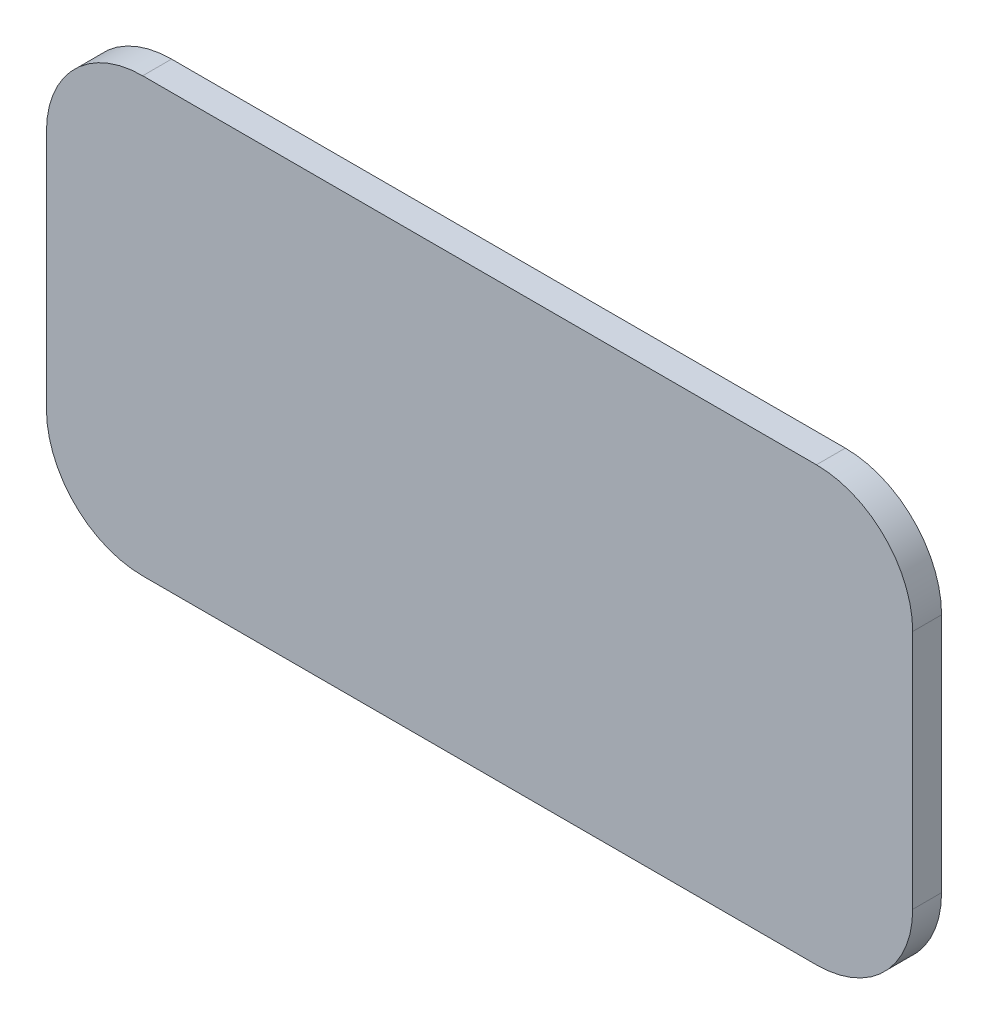
SolidWorks part; units mm, degrees
material "Du"
ref_plane "Front Plane" through (0, 0, 0) normal (0, 0, 1) x (1, 0, 0)
ref_plane "Top Plane" through (0, 0, 0) normal (0, 1, 0) x (1, 0, 0)
ref_plane "Right Plane" through (0, 0, 0) normal (1, 0, 0) x (0, 0, -1)
sketch "Sketch1" plane through (0, 0, 0) normal (0, 0, 1) x (1, 0, 0)
  line L1 (-45, 22.5) -> (45, 22.5)
  line L2 (-45, 22.5) -> (-45, -22.5)
  line L3 (-45, -22.5) -> (45, -22.5)
  line L4 (45, 22.5) -> (45, -22.5)
  line L5 (-45, 22.5) -> (45, -22.5) construction
  line L6 (-45, -22.5) -> (45, 22.5) construction
  point P0 (0, 0)
  dimension "D1" = 90
  dimension "D2" = 45
extrude "Boss-Extrude1" add sketch "Sketch1" along normal blind 3
fillet "Fillet1" radius 10 4 edges at (-45, -22.5, 1.5) (-45, 22.5, 1.5) (45, -22.5, 1.5) (45, 22.5, 1.5)
